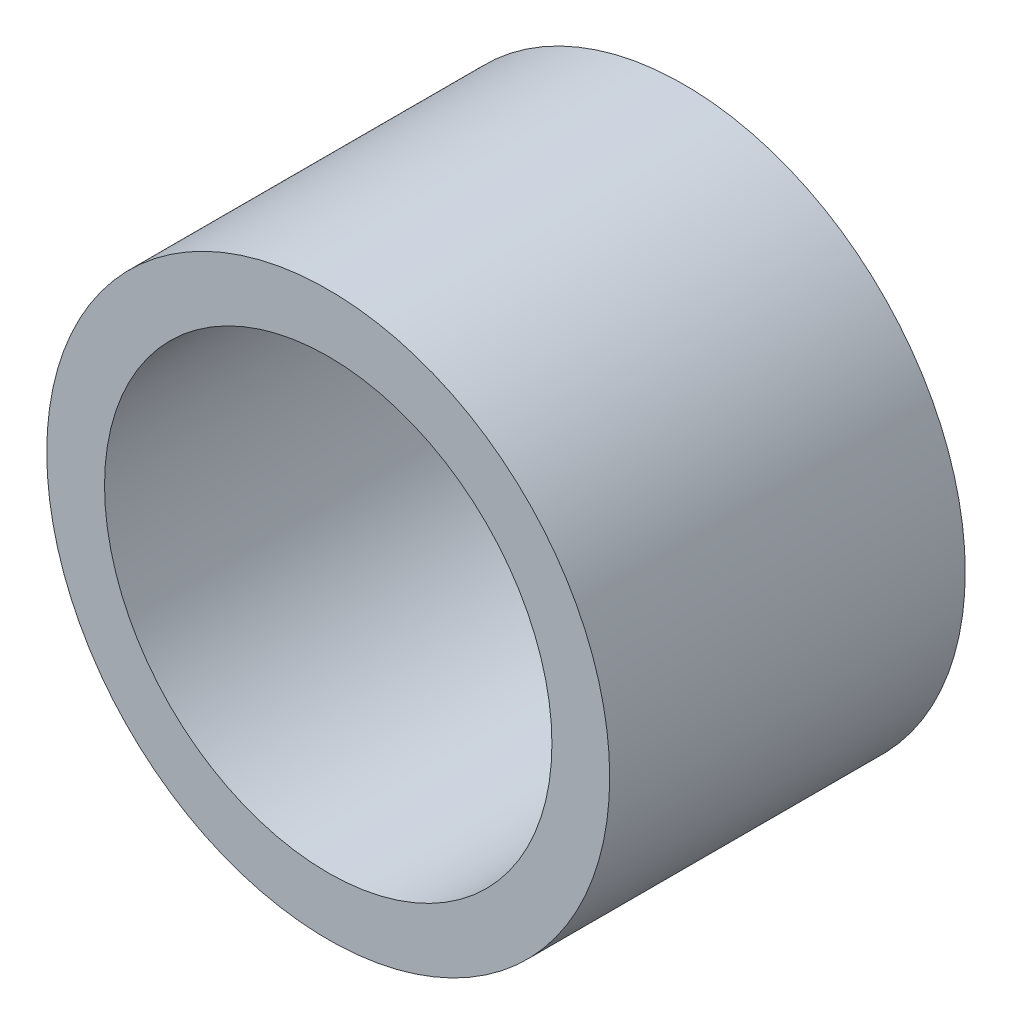
SolidWorks part; units mm, degrees
ref_plane "Front Plane" through (0, 0, 0) normal (0, 0, 1) x (1, 0, 0)
ref_plane "Top Plane" through (0, 0, 0) normal (0, 1, 0) x (1, 0, 0)
ref_plane "Right Plane" through (0, 0, 0) normal (1, 0, 0) x (0, 0, -1)
sketch "Sketch1" plane through (0, 0, 0) normal (0, 0, 1) x (1, 0, 0)
  circle A0 centre (0, 0) radius 15.1
  circle A1 centre (0, 0) radius 19
  dimension "D1" = 30.2
  dimension "D2" = 38
extrude "Boss-Extrude1" add sketch "Sketch1" along normal mid plane 24
